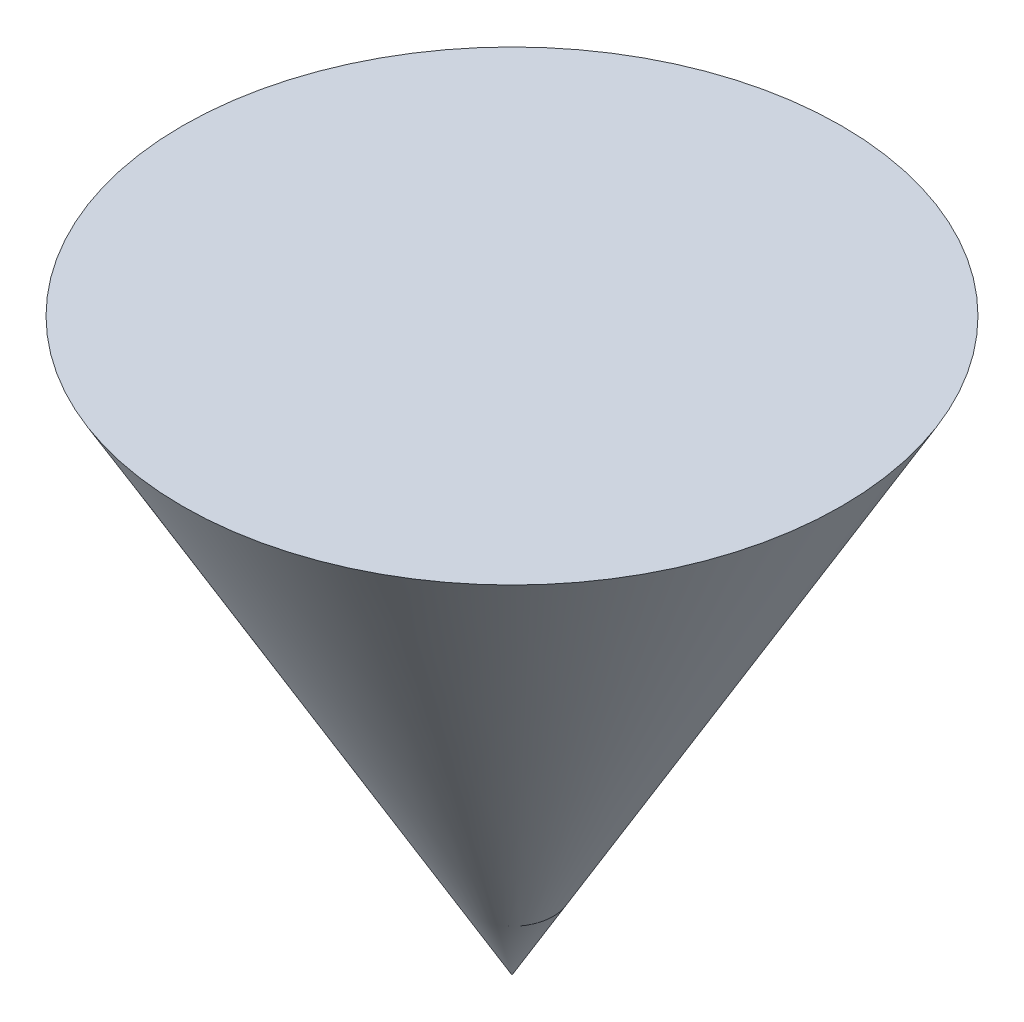
SolidWorks part; units mm, degrees
ref_plane "Front Plane" through (0, 0, 0) normal (0, 0, 1) x (1, 0, 0)
ref_plane "Top Plane" through (0, 0, 0) normal (0, 1, 0) x (1, 0, 0)
ref_plane "Right Plane" through (0, 0, 0) normal (1, 0, 0) x (0, 0, -1)
sketch "Sketch1" plane through (0, 0, 0) normal (0, 0, 1) x (1, 0, 0)
  line L0 (0, 1.1613) -> (0, 30.9865) construction
  line L1 (0, 0) -> (35.4602, 61.4189)
  line L2 (35.4602, 61.4189) -> (0, 61.4189)
  line L3 (0, 0) -> (0, 61.4189)
revolve "camera FOV" add sketch "Sketch1" angle 360 about L0
